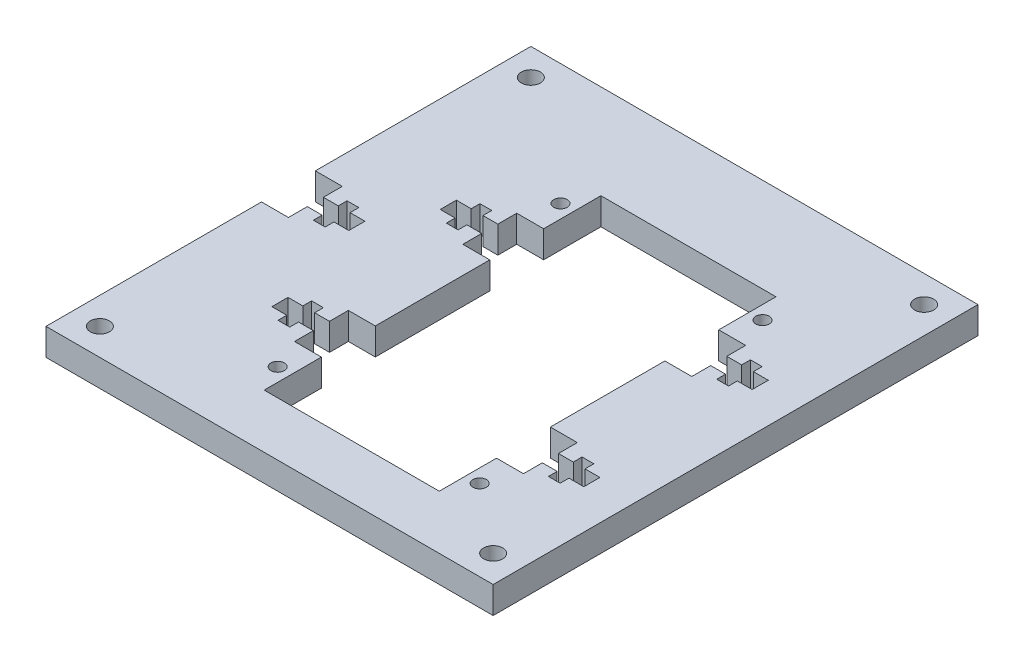
SolidWorks part; units mm, degrees
material "Beech"
ref_plane "Front Plane" through (0, 0, 0) normal (0, 0, 1) x (1, 0, 0)
ref_plane "Top Plane" through (0, 0, 0) normal (0, 1, 0) x (1, 0, 0)
ref_plane "Right Plane" through (0, 0, 0) normal (1, 0, 0) x (0, 0, -1)
sketch "Sketch1" plane through (0, 0, 0) normal (0, 1, 0) x (1, 0, 0)
  line L1 (-52.705, -57.15) -> (52.705, -57.15)
  line L2 (-52.705, -57.15) -> (-52.705, 57.15)
  line L3 (-52.705, 57.15) -> (52.705, 57.15)
  line L4 (52.705, -57.15) -> (52.705, 57.15)
  line L5 (-52.705, -57.15) -> (52.705, 57.15) construction
  line L6 (-52.705, 57.15) -> (52.705, -57.15) construction
  point P0 (0, 0)
  dimension "D1" = 105.41
  dimension "D2" = 114.3
extrude "Boss-Extrude1" add sketch "Sketch1" along normal mid plane 6.35
hole_wizard "#4 Clearance Hole1" [suppressed] positions "Sketch3" profile "Sketch2" hole size "#4" standard "ANSI Inch"
sketch "Sketch3" plane through (0, 3.175, 0) normal (0, 1, 0) x (1, 0, 0)
  line L0 (52.705, 0) -> (-52.705, 0) construction
  line L1 (52.705, -40.005) -> (52.705, 40.005) construction
  line L2 (-52.705, 40.005) -> (-52.705, -40.005) construction
  line L3 (-52.705, 0) -> (0, 40.005) construction
  line L4 (52.705, 40.005) -> (-52.705, 40.005) construction
  line L5 (0, 40.005) -> (0, -40.005) construction
  line L6 (-52.705, -40.005) -> (52.705, -40.005) construction
  point P17 (22.5, 28)
  dimension "D1" = 28
  dimension "D2" = 22.5
sketch "Sketch2" plane through (22.5, 3.175, -28) normal (1, 0, 0) x (0, 0, 1)
  line L0 (0, 0) -> (0, 6.35)
  line L1 (0, 6.35) -> (1.6319, 6.35)
  line L2 (1.6319, 6.35) -> (1.6319, 0)
  line L5 (1.6319, 0) -> (0, 0)
  line L11 (0, -6.35) -> (0, 107.95) construction
  dimension "Thru Hole Dia." = 3.2639
  dimension "Thru Hole Depth" = 6.35
pattern_linear "LPattern1" [suppressed] count 2 spacing 56 count 2 spacing 45
hole_wizard "#8 Clearance Hole1" positions "Sketch5" profile "Sketch4" hole size "#8" standard "ANSI Inch" end condition up to next
sketch "Sketch5" plane through (0, 3.175, 0) normal (0, 1, 0) x (1, 0, 0)
  line L0 (-46.355, 57.15) -> (-46.355, -57.15) construction
  line L1 (52.705, 57.15) -> (-52.705, 57.15) construction
  line L2 (-52.705, -57.15) -> (52.705, -57.15) construction
  line L5 (52.705, 50.8) -> (-52.705, 50.8) construction
  line L6 (52.705, -57.15) -> (52.705, 57.15) construction
  line L7 (-52.705, 57.15) -> (-52.705, -57.15) construction
  point P19 (-46.355, 50.8)
  dimension "D1" = 6.35
  dimension "D2" = 6.35
sketch "Sketch4" plane through (-46.355, 3.175, -50.8) normal (1, 0, 0) x (0, 0, 1)
  line L0 (0, 0) -> (0, 6.351)
  line L1 (0, 6.351) -> (2.2479, 6.351)
  line L2 (2.2479, 6.351) -> (2.2479, 0)
  line L5 (2.2479, 0) -> (0, 0)
  line L11 (0, -6.35) -> (0, 107.95) construction
  dimension "Thru Hole Dia." = 4.4958
  dimension "Thru Hole Depth" = 6.351
mirror "Mirror1" about plane through (0, 0, 0) normal (0, 0, 1) of "#8 Clearance Hole1"
mirror "Mirror2" about plane through (0, 0, 0) normal (1, 0, 0) of "Mirror1", "#8 Clearance Hole1"
sketch "Sketch8" plane through (0, -3.175, 0) normal (0, -1, 0) x (1, 0, 0)
  line L0 (52.705, 57.15) -> (52.705, -57.15) construction
  line L1 (52.705, 41.275) -> (40.005, 41.275)
  line L2 (52.705, 41.275) -> (52.705, 3.175)
  line L3 (52.705, 3.175) -> (40.005, 3.175)
  line L4 (40.005, 41.275) -> (40.005, 3.175)
  line L5 (-52.705, 57.15) -> (52.705, 57.15) construction
  dimension "D1" = 12.7
  dimension "D2" = 15.875
  dimension "D3" = 38.1
extrude "Cut-Extrude1" [suppressed] cut sketch "Sketch8" against normal up to next
hole_wizard "#4 Clearance Hole3" [suppressed] positions "Sketch10" profile "Sketch9" hole size "#4" standard "ANSI Inch"
sketch "Sketch10" plane through (0, 3.175, 0) normal (0, 1, 0) x (1, 0, 0)
  line L0 (49.53, 57.15) -> (49.53, -57.15) construction
  line L1 (52.705, 57.15) -> (-52.705, 57.15) construction
  line L2 (-52.705, -57.15) -> (52.705, -57.15) construction
  line L4 (52.705, -57.15) -> (52.705, 57.15) construction
  point P11 (49.53, 6.35)
  point P13 (49.53, -12.7)
  dimension "D1" = 3.175
  dimension "D2" = 50.8
  dimension "D3" = 19.05
sketch "Sketch9" plane through (49.53, 3.175, -6.35) normal (1, 0, 0) x (0, 0, 1)
  line L0 (0, 0) -> (0, 6.35)
  line L1 (0, 6.35) -> (1.6319, 6.35)
  line L2 (1.6319, 6.35) -> (1.6319, 0)
  line L5 (1.6319, 0) -> (0, 0)
  line L11 (0, -6.35) -> (0, 107.95) construction
  dimension "Thru Hole Dia." = 3.2639
  dimension "Thru Hole Depth" = 6.35
sketch "Sketch11" [suppressed] plane through (0, 3.175, 0) normal (0, 1, 0) x (1, 0, 0)
  line L0 (49.53, -12.7) -> (49.53, 6.35) construction
ref_plane "Plane1" [suppressed] through (49.53, 0, 0) normal (1, 0, 0) x (0, 0, -1)
sketch "Sketch14" plane through (0, 3.175, 0) normal (0, 1, 0) x (1, 0, 0)
  line L0 (27.305, 57.15) -> (40.005, 57.15)
  line L1 (27.305, 57.15) -> (27.305, 50.8)
  line L2 (40.005, 57.15) -> (40.005, 50.8)
  line L3 (35.5537, 44.5214) -> (35.5537, 41.021)
  line L4 (37.6238, 44.5214) -> (35.5537, 44.5214)
  line L5 (37.6238, 47.2996) -> (37.6238, 44.5214)
  line L6 (35.5537, 47.2996) -> (37.6238, 47.2996)
  line L7 (31.7564, 44.5214) -> (31.7564, 41.021)
  line L8 (29.6863, 44.5214) -> (31.7564, 44.5214)
  line L9 (29.6863, 47.2996) -> (29.6863, 44.5214)
  line L10 (31.7564, 47.2996) -> (29.6863, 47.2996)
  line L11 (31.7564, 50.8) -> (31.7564, 47.2996)
  line L12 (35.5537, 41.021) -> (31.7564, 41.021)
  line L13 (35.5537, 50.8) -> (35.5537, 47.2996)
  line L14 (35.5537, 50.8) -> (40.005, 50.8)
  line L15 (27.305, 50.8) -> (31.7564, 50.8)
  line L16 (33.655, 57.15) -> (33.655, 41.021) construction
  line L17 (52.705, 57.15) -> (-52.705, 57.15) construction
  line L21 (52.705, -4.445) -> (52.705, 57.15) construction
  dimension "D1" = 12.7
  dimension "D2" = 6.35
  dimension "D3" = 3.7973
  dimension "D4" = 3.9688
  dimension "D5" = 2.7781
  dimension "D6" = 9.779
  dimension "D7" = 19.05
extrude "Cut-Extrude3" [suppressed] cut sketch "Sketch14" against normal up to next
pattern_linear "LPattern4" [suppressed] count 2 spacing 25.4
ref_plane "Plane4" [suppressed] through (0, 0, -53.975) normal (0, 0, -1) x (-1, 0, 0)
ref_plane "Plane5" [suppressed] through (20.955, 0, 0) normal (1, 0, 0) x (0, 0, -1)
sketch "Sketch15" plane through (0, -3.175, 0) normal (0, -1, 0) x (1, 0, 0)
  line L0 (0, 0) -> (-52.705, 0) construction
  line L1 (-52.705, -57.15) -> (-52.705, 57.15) construction
  line L2 (-13.97, 44.45) -> (27.305, 44.45)
  line L3 (27.305, -34.925) -> (-13.97, -34.925)
  line L4 (27.305, -34.925) -> (27.305, 44.45)
  line L6 (-13.97, -34.925) -> (-13.97, 44.45)
  point P5 (-1.27, 0)
  dimension "D1" = 1.27
  dimension "D2" = 41.275
  dimension "D3" = 34.925
  dimension "D4" = 12.7
  dimension "D5" = 44.45
extrude "Cut-Extrude4" cut sketch "Sketch15" against normal up to next contours L6 L2 L4 L3
sketch "Sketch16" plane through (0, 3.175, 0) normal (0, 1, 0) x (1, 0, 0)
  line L0 (-52.705, -6.35) -> (-52.705, 6.35)
  line L1 (-52.705, 6.35) -> (-46.355, 6.35)
  line L2 (-46.355, 6.35) -> (-46.355, 1.8986)
  line L3 (-46.355, 1.8986) -> (-42.8546, 1.8986)
  line L4 (-42.8546, 1.8986) -> (-42.8546, 3.9687)
  line L5 (-42.8546, 3.9687) -> (-40.0764, 3.9687)
  line L6 (-40.0764, 3.9687) -> (-40.0764, 1.8986)
  line L7 (-40.0764, 1.8986) -> (-36.576, 1.8986)
  line L8 (-36.576, 1.8986) -> (-36.576, -1.8986)
  line L9 (-40.0764, -1.8986) -> (-36.576, -1.8986)
  line L10 (-40.0764, -3.9687) -> (-40.0764, -1.8986)
  line L11 (-42.8546, -3.9687) -> (-40.0764, -3.9687)
  line L12 (-42.8546, -1.8986) -> (-42.8546, -3.9687)
  line L13 (-46.355, -1.8986) -> (-42.8546, -1.8986)
  line L14 (-46.355, -6.35) -> (-46.355, -1.8986)
  line L15 (-52.705, -6.35) -> (-46.355, -6.35)
  line L17 (0, 0) -> (-52.705, 0) construction
  line L18 (-52.705, 57.15) -> (-52.705, -57.15) construction
  point P11 (-36.576, 0)
  point P12 (-52.705, 0)
  dimension "D1" = 12.7
  dimension "D2" = 3.7973
  dimension "D3" = 6.35
  dimension "D4" = 9.779
  dimension "D5" = 2.7781
  dimension "D6" = 3.9688
extrude "Cut-Extrude5" cut sketch "Sketch16" against normal up to next
sketch "Sketch17" plane through (0, 3.175, 0) normal (0, 1, 0) x (1, 0, 0)
  line L0 (-13.97, -44.45) -> (-13.97, 34.925) construction
  line L1 (27.305, -44.45) -> (27.305, 34.925) construction
  line L2 (-13.97, 34.925) -> (27.305, 34.925) construction
  line L3 (27.305, -24.6062) -> (43.434, -24.6062) construction
  line L4 (27.305, -44.45) -> (-13.97, -44.45) construction
  line L5 (-13.97, 15.0812) -> (-30.099, 15.0812) construction
  line L6 (-20.32, 8.7312) -> (-13.97, 8.7312)
  line L7 (-20.32, 8.7312) -> (-20.32, 13.1826)
  line L8 (-20.32, 21.4312) -> (-13.97, 21.4312)
  line L9 (-13.97, 8.7312) -> (-13.97, 21.4312)
  line L10 (-20.32, 8.7312) -> (-13.97, 21.4312) construction
  line L11 (-20.32, 21.4312) -> (-13.97, 8.7312) construction
  line L12 (-30.099, 16.9799) -> (-30.099, 13.1826)
  line L13 (-30.099, 16.9799) -> (-26.5986, 16.9799)
  line L14 (-26.5986, 16.9799) -> (-26.5986, 19.05)
  line L15 (-26.5986, 19.05) -> (-23.8204, 19.05)
  line L16 (-23.8204, 19.05) -> (-23.8204, 16.9799)
  line L17 (-23.8204, 16.9799) -> (-20.32, 16.9799)
  line L18 (-23.8204, 11.1125) -> (-23.8204, 13.1826)
  line L19 (-23.8204, 13.1826) -> (-20.32, 13.1826)
  line L20 (-26.5986, 11.1125) -> (-23.8204, 11.1125)
  line L21 (-26.5986, 13.1826) -> (-26.5986, 11.1125)
  line L22 (-30.099, 13.1826) -> (-26.5986, 13.1826)
  line L23 (-20.32, 16.9799) -> (-20.32, 21.4312)
  line L24 (6.6675, 34.925) -> (6.6675, -44.45) construction
  line L25 (-13.97, -4.7625) -> (27.305, -4.7625) construction
  line L26 (33.655, -18.2562) -> (27.305, -30.9562) construction
  line L27 (33.655, -30.9562) -> (27.305, -18.2562) construction
  line L28 (33.655, 21.4313) -> (27.305, 8.7313) construction
  line L29 (33.655, 8.7313) -> (27.305, 21.4313) construction
  line L30 (27.305, 15.0813) -> (43.434, 15.0813) construction
  line L31 (33.655, -18.2562) -> (27.305, -18.2562)
  line L32 (33.655, -18.2562) -> (33.655, -22.7076)
  line L33 (33.655, -30.9562) -> (27.305, -30.9562)
  line L34 (27.305, -18.2562) -> (27.305, -30.9562)
  line L35 (43.434, -26.5049) -> (43.434, -22.7076)
  line L36 (43.434, -26.5049) -> (39.9336, -26.5049)
  line L37 (39.9336, -26.5049) -> (39.9336, -28.575)
  line L38 (39.9336, -28.575) -> (37.1554, -28.575)
  line L39 (37.1554, -28.575) -> (37.1554, -26.5049)
  line L40 (37.1554, -26.5049) -> (33.655, -26.5049)
  line L41 (37.1554, -20.6375) -> (37.1554, -22.7076)
  line L42 (37.1554, -22.7076) -> (33.655, -22.7076)
  line L43 (39.9336, -20.6375) -> (37.1554, -20.6375)
  line L44 (39.9336, -22.7076) -> (39.9336, -20.6375)
  line L45 (-20.32, -30.9563) -> (-13.97, -18.2563) construction
  line L46 (-20.32, -18.2563) -> (-13.97, -30.9563) construction
  line L47 (-13.97, -24.6063) -> (-30.099, -24.6063) construction
  line L48 (-20.32, -26.5049) -> (-20.32, -30.9563)
  line L49 (-30.099, -22.7076) -> (-26.5986, -22.7076)
  line L50 (-26.5986, -22.7076) -> (-26.5986, -20.6375)
  line L51 (-26.5986, -20.6375) -> (-23.8204, -20.6375)
  line L52 (-23.8204, -22.7076) -> (-20.32, -22.7076)
  line L53 (-23.8204, -20.6375) -> (-23.8204, -22.7076)
  line L54 (-23.8204, -26.5049) -> (-20.32, -26.5049)
  line L55 (-23.8204, -28.575) -> (-23.8204, -26.5049)
  line L56 (-26.5986, -28.575) -> (-23.8204, -28.575)
  line L57 (-26.5986, -26.5049) -> (-26.5986, -28.575)
  line L58 (-30.099, -26.5049) -> (-26.5986, -26.5049)
  line L59 (-30.099, -26.5049) -> (-30.099, -22.7076)
  line L60 (-13.97, -18.2563) -> (-13.97, -30.9563)
  line L61 (-20.32, -30.9563) -> (-13.97, -30.9563)
  line L62 (-20.32, -18.2563) -> (-20.32, -22.7076)
  line L63 (-20.32, -18.2563) -> (-13.97, -18.2563)
  line L64 (43.434, -22.7076) -> (39.9336, -22.7076)
  line L65 (33.655, -26.5049) -> (33.655, -30.9562)
  line L66 (33.655, 16.9799) -> (33.655, 21.4313)
  line L67 (43.434, 13.1826) -> (39.9336, 13.1826)
  line L68 (39.9336, 13.1826) -> (39.9336, 11.1125)
  line L69 (39.9336, 11.1125) -> (37.1554, 11.1125)
  line L70 (37.1554, 13.1826) -> (33.655, 13.1826)
  line L71 (37.1554, 11.1125) -> (37.1554, 13.1826)
  line L72 (37.1554, 16.9799) -> (33.655, 16.9799)
  line L73 (37.1554, 19.05) -> (37.1554, 16.9799)
  line L74 (39.9336, 19.05) -> (37.1554, 19.05)
  line L75 (39.9336, 16.9799) -> (39.9336, 19.05)
  line L76 (43.434, 16.9799) -> (39.9336, 16.9799)
  line L77 (43.434, 16.9799) -> (43.434, 13.1826)
  line L78 (27.305, 8.7313) -> (27.305, 21.4313)
  line L79 (33.655, 21.4313) -> (27.305, 21.4313)
  line L80 (33.655, 8.7313) -> (33.655, 13.1826)
  line L81 (33.655, 8.7313) -> (27.305, 8.7313)
  circle A0 centre (-17.145, 28.575) radius 1.5875
  circle A1 centre (-17.145, -38.1) radius 1.5875
  circle A2 centre (30.48, -38.1) radius 1.5875
  circle A3 centre (30.48, 28.575) radius 1.5875
  point P12 (-30.099, 15.0812)
  point P24 (-17.145, 15.0812)
  point P77 (-17.145, -24.6063)
  point P95 (30.48, -24.6062)
  point P96 (30.48, 15.0813)
  dimension "D2" = 3.175
  dimension "D1" = 3.175
  dimension "D4" = 6.35
  dimension "D5" = 6.35
  dimension "D7" = 6.35
  dimension "D8" = 12.7
  dimension "D9" = 19.8438
  dimension "D10" = 3.7973
  dimension "D11" = 9.779
  dimension "D12" = 2.7781
  dimension "D13" = 3.9688
extrude "Cut-Extrude6" cut sketch "Sketch17" against normal blind 6.35
